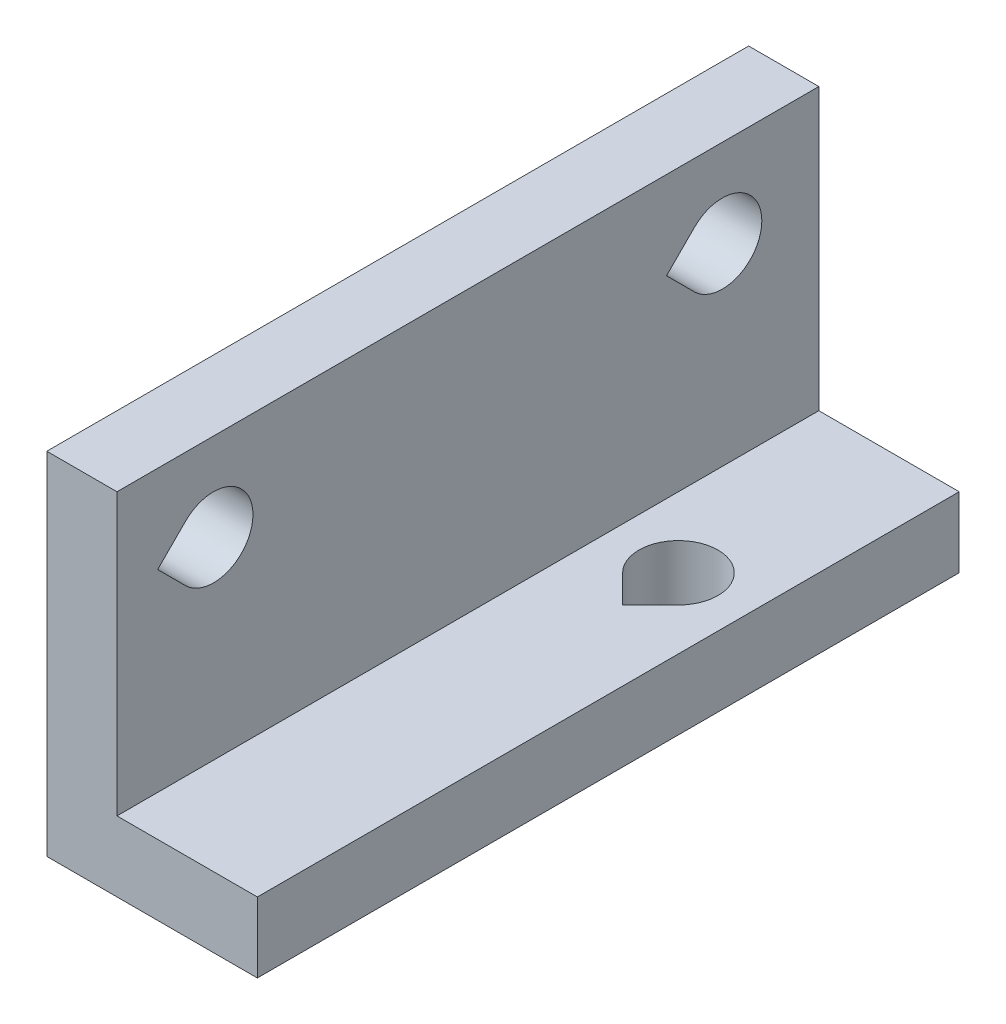
SolidWorks part; units mm, degrees
material "Printed PLA"
ref_plane "Front Plane" through (0, 0, 0) normal (0, 0, 1) x (1, 0, 0)
ref_plane "Top Plane" through (0, 0, 0) normal (0, 1, 0) x (1, 0, 0)
ref_plane "Right Plane" through (0, 0, 0) normal (1, 0, 0) x (0, 0, -1)
sketch "Sketch1" plane through (0, 0, 0) normal (0, 0, 1) x (1, 0, 0)
  line L0 (-15, 0) -> (15, 0)
  line L1 (15, 0) -> (15, 4)
  line L2 (15, 4) -> (7, 4)
  line L3 (7, 4) -> (7, 20)
  line L4 (7, 20) -> (3, 20)
  line L5 (3, 20) -> (3, 4)
  line L6 (3, 4) -> (-3, 4)
  line L7 (-3, 4) -> (-3, 20)
  line L8 (-3, 20) -> (-7, 20)
  line L9 (-7, 20) -> (-7, 4)
  line L10 (-7, 4) -> (-15, 4)
  line L11 (-15, 4) -> (-15, 0)
  dimension "D1" = 30
  dimension "D2" = 4
  dimension "D3" = 6
  dimension "D4" = 4
  dimension "D5" = 20
extrude "Boss-Extrude1" add sketch "Sketch1" along normal blind 40
sketch "Sketch2" plane through (0, 4, 0) normal (0, 1, 0) x (1, 0, 0)
  line L0 (11, -12) -> (-11, -12) construction
  line L1 (0, -12) -> (0, 0) construction
  line L2 (3, 0) -> (-3, 0) construction
  line L3 (-12.591, -13.591) -> (-11, -15.182)
  line L4 (-11, -15.182) -> (-9.409, -13.591)
  line L5 (-11, -15.182) -> (-11, -12) construction
  line L6 (9.409, -13.591) -> (11, -15.182)
  line L7 (11, -15.182) -> (12.591, -13.591)
  line L8 (11, -15.182) -> (11, -12) construction
  arc A0 (-9.409, -13.591) -> (-12.591, -13.591) centre (-11, -12) ccw
  arc A1 (12.591, -13.591) -> (9.409, -13.591) centre (11, -12) ccw
  dimension "D2" = 4.5
  dimension "D1" = 22
  dimension "D3" = 12
extrude "Cut-Extrude1" cut sketch "Sketch2" against normal through all
sketch "Sketch3" plane through (7, 0, 0) normal (1, 0, 0) x (0, 0, -1)
  line L0 (-40, 0) -> (0, 0) construction
  line L2 (-7.091, 16.591) -> (-8.682, 15)
  line L3 (-8.682, 15) -> (-7.091, 13.409)
  line L4 (-8.682, 15) -> (-5.5, 15) construction
  line L5 (0, 4) -> (0, 20) construction
  line L6 (-5.5, 15) -> (-34.5, 15) construction
  line L7 (-36.091, 16.591) -> (-37.682, 15)
  line L8 (-37.682, 15) -> (-36.091, 13.409)
  line L9 (-37.682, 15) -> (-34.5, 15) construction
  arc A0 (-7.091, 13.409) -> (-7.091, 16.591) centre (-5.5, 15) ccw
  arc A1 (-36.091, 13.409) -> (-36.091, 16.591) centre (-34.5, 15) ccw
  dimension "D1" = 4.5
  dimension "D3" = 5.5
  dimension "D2" = 15
  dimension "D5" = 29
  dimension "D4" = 2
extrude "Cut-Extrude2" cut sketch "Sketch3" against normal through all
sketch "Sketch8" plane through (0, 4, 0) normal (0, 1, 0) x (1, 0, 0)
  line L1 (-3, 0) -> (3, 0)
  line L2 (-3, 0) -> (-3, -40)
  line L3 (-3, -40) -> (3, -40)
  line L4 (3, 0) -> (3, -40)
extrude "Cut-Extrude4" cut sketch "Sketch8" against normal through all
delete or keep bodies "Body-Delete1" type delete bodies bodies 110
